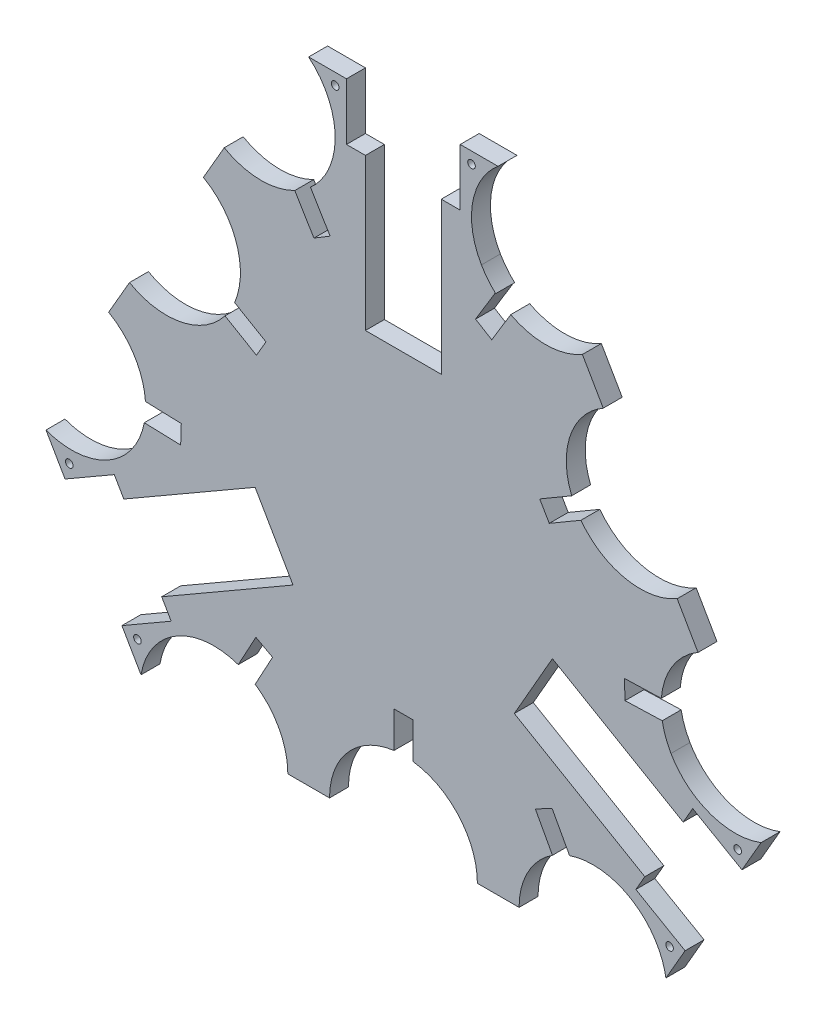
SolidWorks part; units mm, degrees
ref_plane "Plan de face" through (0, 0, 0) normal (0, 0, 1) x (1, 0, 0)
ref_plane "Plan de dessus" through (0, 0, 0) normal (0, 1, 0) x (1, 0, 0)
ref_plane "Plan de droite" through (0, 0, 0) normal (1, 0, 0) x (0, 0, -1)
sketch "Model" plane through (0, 0, 0) normal (0, 0, 1) x (1, 0, 0)
  line L662 (118.6164, -1154.7177) -> (127.9304, -1137.5509)
  line L663 (127.9304, -1137.5509) -> (136.72, -1142.3198)
  line L664 (136.72, -1142.3198) -> (127.5618, -1159.1996)
  line L665 (144.7752, -1191.5513) -> (166.7752, -1191.5513)
  line L666 (200.7752, -1152.8693) -> (200.7752, -1133.8449)
  line L667 (200.7752, -1133.8449) -> (210.7753, -1133.8449)
  line L668 (210.7753, -1133.8449) -> (210.7753, -1152.8693)
  line L669 (244.7753, -1191.5513) -> (266.7753, -1191.5513)
  line L670 (284.3929, -1158.9336) -> (275.3788, -1142.3198)
  line L671 (275.3788, -1142.3198) -> (284.1684, -1137.5509)
  line L672 (284.1684, -1137.5509) -> (293.3961, -1154.5585)
  line L673 (344.2368, -1185.0738) -> (354.3495, -1167.558)
  line L674 (354.3495, -1167.558) -> (328.3719, -1152.5598)
  line L675 (328.3719, -1152.5598) -> (333.1301, -1144.3183)
  line L676 (333.1301, -1144.3183) -> (264.2714, -1104.2143)
  line L677 (264.2714, -1104.2143) -> (284.3684, -1069.0978)
  line L678 (284.3684, -1069.0978) -> (353.3599, -1109.2793)
  line L679 (353.3599, -1109.2793) -> (358.3718, -1100.5983)
  line L680 (358.3718, -1100.5983) -> (384.3494, -1115.5964)
  line L681 (384.3494, -1115.5964) -> (394.4221, -1098.1497)
  line L682 (342.2811, -1068.5144) -> (322.6668, -1069.1396)
  line L683 (322.6668, -1069.1396) -> (322.3483, -1059.1447)
  line L684 (322.3483, -1059.1447) -> (341.8054, -1058.5245)
  line L685 (361.1808, -1027.8726) -> (350.1807, -1008.82)
  line L686 (299.413, -998.3554) -> (282.7063, -1008.1211)
  line L687 (282.7063, -1008.1211) -> (277.6598, -999.4879)
  line L688 (277.6598, -999.4879) -> (294.5118, -989.6372)
  line L689 (311.1809, -941.27) -> (300.1809, -922.2175)
  line L690 (262.3971, -922.8937) -> (252.3743, -939.4373)
  line L691 (252.3743, -939.4373) -> (243.8215, -934.2556)
  line L692 (243.8215, -934.2556) -> (254.1849, -917.15)
  line L693 (254.1849, -917.15) -> (254.439, -917.3039)
  line L694 (255.6733, -858.5099) -> (247.9625, -858.5099)
  line L695 (247.9625, -858.5099) -> (235.7176, -858.5099)
  line L696 (235.7176, -858.5099) -> (235.7176, -888.5099)
  line L697 (235.7176, -888.5099) -> (225.7175, -888.5099)
  line L698 (225.7175, -888.5099) -> (225.7175, -968.5099)
  line L699 (225.7175, -968.5099) -> (185.7176, -968.5099)
  line L700 (185.7176, -968.5099) -> (185.7176, -888.5099)
  line L701 (185.7176, -888.5099) -> (175.7175, -888.5099)
  line L702 (175.7175, -888.5099) -> (175.7175, -858.5099)
  line L703 (175.7175, -858.5099) -> (163.4726, -858.5099)
  line L704 (163.4726, -858.5099) -> (155.7618, -858.5099)
  line L705 (156.5681, -917.6896) -> (156.7309, -917.591)
  line L706 (156.7309, -917.591) -> (167.0942, -934.6965)
  line L707 (167.0942, -934.6965) -> (158.5415, -939.8782)
  line L708 (158.5415, -939.8782) -> (148.4396, -923.2044)
  line L709 (111.2542, -922.2175) -> (100.2542, -941.27)
  line L710 (116.676, -990.2373) -> (133.2558, -999.9289)
  line L711 (133.2558, -999.9289) -> (128.2093, -1008.5621)
  line L712 (128.2093, -1008.5621) -> (111.6322, -998.8721)
  line L713 (61.2542, -1008.82) -> (50.2542, -1027.8726)
  line L714 (69.6666, -1058.9832) -> (88.5674, -1059.5857)
  line L715 (88.5674, -1059.5857) -> (88.2488, -1069.5806)
  line L716 (88.2488, -1069.5806) -> (69.0689, -1068.9692)
  line L717 (17.2057, -1098.2221) -> (21.0894, -1104.9488)
  line L718 (21.0894, -1104.9488) -> (27.2432, -1115.6074)
  line L719 (27.2432, -1115.6074) -> (53.2397, -1100.5983)
  line L720 (53.2397, -1100.5983) -> (58.2396, -1109.2586)
  line L721 (58.2396, -1109.2586) -> (127.5216, -1069.2586)
  line L722 (127.5216, -1069.2586) -> (147.5216, -1103.8996)
  line L723 (147.5216, -1103.8996) -> (78.2396, -1143.8996)
  line L724 (78.2396, -1143.8996) -> (83.2396, -1152.5598)
  line L725 (83.2396, -1152.5598) -> (57.2432, -1167.5689)
  line L726 (57.2432, -1167.5689) -> (63.4324, -1178.2888)
  line L727 (63.4324, -1178.2888) -> (63.4324, -1178.289)
  line L728 (63.4324, -1178.289) -> (67.3217, -1185.0257)
  circle A0 centre (65.4514, -1169.7082) radius 2
  circle A1 centre (29.4945, -1107.4292) radius 2
  circle A2 centre (169.7608, -864.5305) radius 2
  circle A3 centre (241.6744, -864.5305) radius 2
  circle A4 centre (382.1169, -1107.4293) radius 2
  circle A6 centre (346.1602, -1169.7083) radius 2
  spline S707 degree 3 poles (67.3217, -1185.0257) (70.4273, -1166.5936) (86.4601, -1152.5513) (105.7752, -1152.5513) knots 0 0 0 0 1 1 1 1
  spline S708 degree 3 poles (105.7752, -1152.5513) (110.2746, -1152.5513) (114.595, -1153.3158) (118.6164, -1154.7177) knots 1 1 1 1 2 2 2 2
  spline S709 degree 3 poles (127.5618, -1159.1996) (137.9463, -1166.2065) (144.7752, -1178.0813) (144.7752, -1191.5513) knots 5 5 5 5 6 6 6 6
  spline S710 degree 3 poles (166.7752, -1191.5513) (166.7752, -1171.7063) (181.5976, -1155.3237) (200.7752, -1152.8693) knots 7 7 7 7 8 8 8 8
  spline S711 degree 3 poles (210.7753, -1152.8693) (229.9529, -1155.3237) (244.7753, -1171.7063) (244.7753, -1191.5513) knots 11 11 11 11 12 12 12 12
  spline S712 degree 3 poles (266.7753, -1191.5513) (266.7753, -1177.9081) (273.7825, -1165.9033) (284.3929, -1158.9336) knots 13 13 13 13 14 14 14 14
  spline S713 degree 3 poles (293.3961, -1154.5585) (297.2856, -1153.2575) (301.4478, -1152.5513) (305.7752, -1152.5513) knots 17 17 17 17 18 18 18 18
  spline S714 degree 3 poles (305.7752, -1152.5513) (325.1072, -1152.5513) (341.151, -1166.6181) (344.2368, -1185.0738) knots 18 18 18 18 19 19 19 19
  spline S715 degree 3 poles (394.4221, -1098.1497) (376.8685, -1104.7819) (356.594, -1097.9278) (346.9058, -1081.1476) knots 28 28 28 28 29 29 29 29
  spline S716 degree 3 poles (346.9058, -1081.1476) (344.5792, -1077.1177) (343.0553, -1072.8451) (342.2811, -1068.5144) knots 29 29 29 29 30 30 30 30
  spline S717 degree 3 poles (341.8054, -1058.5245) (342.8076, -1046.187) (349.6499, -1034.53) (361.1808, -1027.8726) knots 33 33 33 33 34 34 34 34
  spline S718 degree 3 poles (350.1807, -1008.82) (332.8616, -1018.8192) (311.0631, -1014.0226) (299.413, -998.3554) knots 35 35 35 35 36 36 36 36
  spline S719 degree 3 poles (294.5118, -989.6372) (287.327, -971.8923) (294.1287, -951.1151) (311.1809, -941.27) knots 39 39 39 39 40 40 40 40
  spline S720 degree 3 poles (300.1809, -922.2175) (288.1117, -929.1856) (273.8672, -928.9671) (262.3971, -922.8937) knots 43 43 43 43 44 44 44 44
  spline S721 degree 3 poles (254.439, -917.3039) (251.5315, -914.6591) (248.9762, -911.5284) (246.9059, -907.9425) knots 48 48 48 48 49 49 49 49
  spline S722 degree 3 poles (246.9059, -907.9425) (237.277, -891.265) (241.3676, -870.4333) (255.6733, -858.5099) knots 49 49 49 49 50 50 50 50
  spline S723 degree 3 poles (155.7618, -858.5099) (170.0675, -870.4333) (174.1581, -891.265) (164.5292, -907.9425) knots 61 61 61 61 62 62 62 62
  spline S724 degree 3 poles (164.5292, -907.9425) (162.3578, -911.7037) (159.6535, -914.9655) (156.5681, -917.6896) knots 62 62 62 62 63 63 63 63
  spline S725 degree 3 poles (148.4396, -923.2044) (137.0752, -928.9728) (123.1145, -929.0649) (111.2542, -922.2175) knots 67 67 67 67 68 68 68 68
  spline S726 degree 3 poles (100.2542, -941.27) (117.499, -951.2262) (124.2617, -972.3631) (116.676, -990.2373) knots 71 71 71 71 72 72 72 72
  spline S727 degree 3 poles (111.6322, -998.8721) (99.8908, -1014.1275) (78.3818, -1018.7086) (61.2542, -1008.82) knots 75 75 75 75 76 76 76 76
  spline S728 degree 3 poles (50.2542, -1027.8726) (61.9282, -1034.6125) (68.7988, -1046.4764) (69.6666, -1058.9832) knots 79 79 79 79 80 80 80 80
  spline S729 degree 3 poles (69.0689, -1068.9692) (68.271, -1073.1441) (66.7744, -1077.2589) (64.5293, -1081.1476) knots 83 83 83 83 84 84 84 84
  spline S730 degree 3 poles (64.5293, -1081.1476) (54.8766, -1097.8664) (34.7149, -1104.7317) (17.2057, -1098.2221) knots 84 84 84 84 85 85 85 85
  dimension "D2" = 4
  dimension "D3" = 4
  dimension "D4" = 4
  dimension "D5" = 4
  dimension "D6" = 4
  dimension "D7" = 4
  dimension "D1" = 40
extrude "Boss.-Extru.1" add sketch "Model" along normal blind 10
